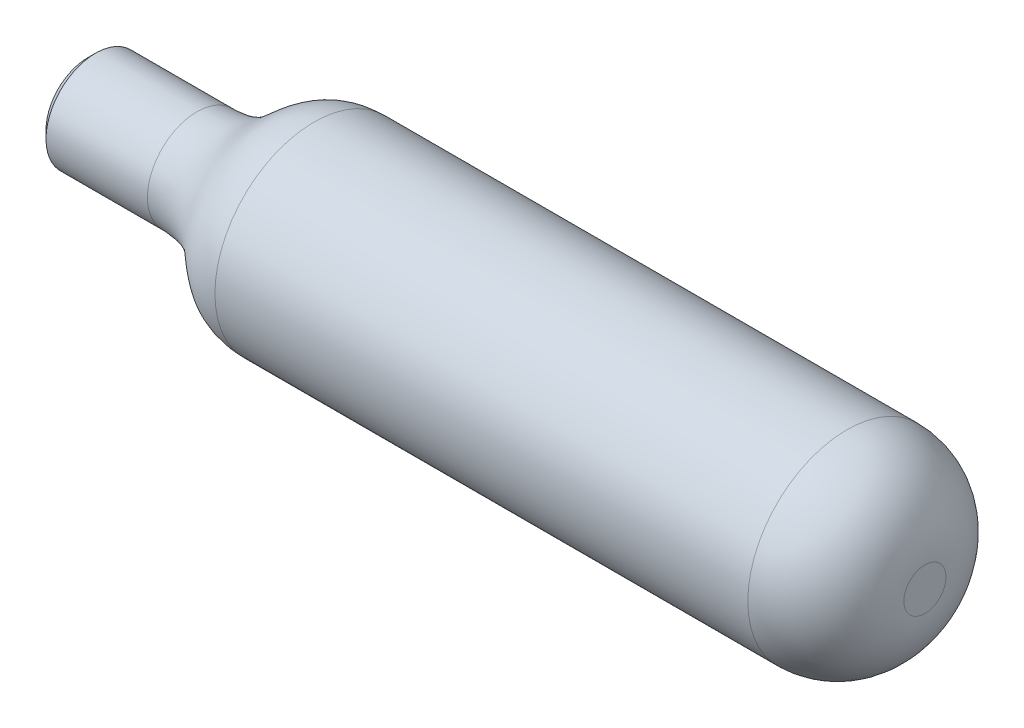
SolidWorks part; units mm, degrees
ref_plane "Front Plane" through (0, 0, 0) normal (0, 0, 1) x (1, 0, 0)
ref_plane "Top Plane" through (0, 0, 0) normal (0, 1, 0) x (1, 0, 0)
ref_plane "Right Plane" through (0, 0, 0) normal (1, 0, 0) x (0, 0, -1)
sketch "revolution body" plane through (0, 0, 0) normal (0, 0, 1) x (1, 0, 0)
  line L0 (-67.0343, 8.8194) -> (-54.0343, 8.8194)
  line L1 (-39.0343, 15.1694) -> (29.2657, 15.1694)
  line L2 (-68.0343, 7.8194) -> (-67.0343, 8.8194)
  line L3 (-68.0343, 2.4694) -> (39.2657, 2.4694)
  line L4 (39.2657, 5.1694) -> (39.2657, 2.4694)
  line L10 (-68.0343, 2.4694) -> (-68.0343, 7.8194)
  arc A0 (29.2657, 15.1694) -> (39.2657, 5.1694) centre (29.2657, 5.1694) cw
  spline S0 degree 3 poles (-54.0343, 8.8194) (-45.6399, 8.7161) (-46.4251, 15.0317) (-39.0343, 15.1694) knots 0 0 0 0 1 1 1 1
  point P9 (-68.0343, 8.8194)
  dimension "D3" = 10
  dimension "D1" = 107.3
  dimension "D2" = 14
  dimension "D4" = 6.35
  dimension "D5" = 12.7
  dimension "D6" = 15
revolve "Revolve1" add sketch "revolution body" angle 360 about L3
